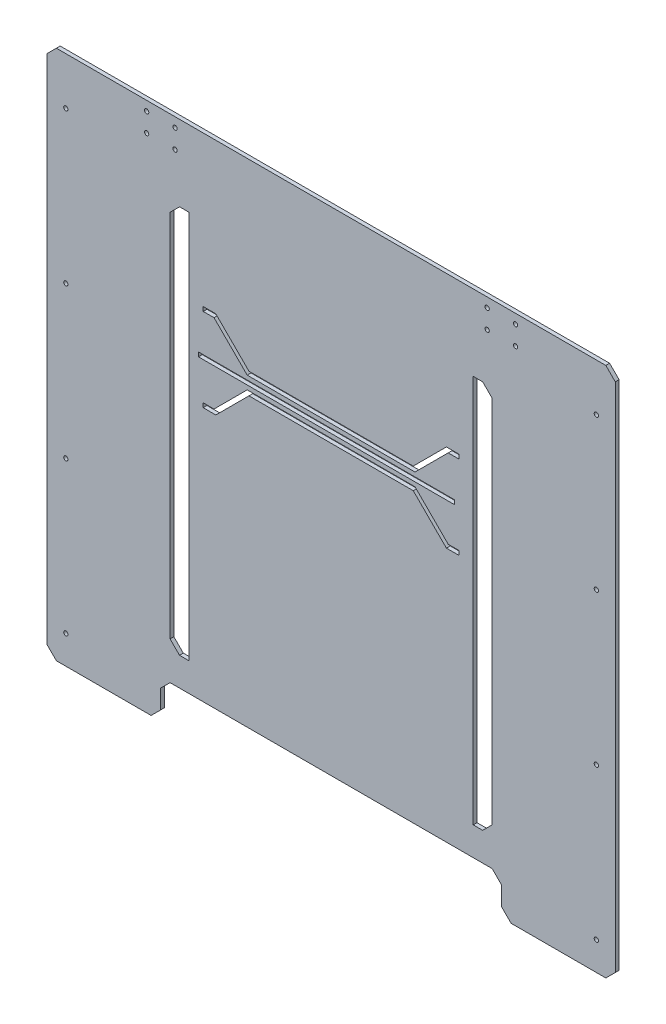
SolidWorks part; units mm, degrees
ref_plane "Front Plane" through (0, 0, 0) normal (0, 0, 1) x (1, 0, 0)
ref_plane "Top Plane" through (0, 0, 0) normal (0, 1, 0) x (1, 0, 0)
ref_plane "Right Plane" through (0, 0, 0) normal (1, 0, 0) x (0, 0, -1)
sketch "Sketch1" plane through (0, 0, 0) normal (0, 0, 1) x (1, 0, 0)
  line L0 (440.3197, -451.5188) -> (440.3197, -431.5188)
  line L1 (430.3197, -421.5188) -> (310.3197, -421.5188)
  line L2 (560.3197, -5.0048) -> (560.3197, 98.4812)
  line L3 (80.3197, -431.5188) -> (80.3197, -451.5188)
  line L4 (560.3197, 98.4812) -> (540.3197, 98.4812)
  line L5 (531.5264, 93.7193) -> (531.5264, -420.0048) construction
  line L6 (560.3197, -5.0048) -> (560.3197, -420.0048)
  line L7 (0.3197, 98.4812) -> (540.3197, 98.4812)
  line L8 (2.3197, -461.5188) -> (70.3197, -461.5188)
  line L9 (450.3197, -461.5188) -> (540.3197, -461.5188)
  line L10 (440.3197, -431.5188) -> (430.3197, -421.5188)
  line L11 (503.536, -23.973) -> (503.536, -80.4204) construction
  line L12 (-39.6803, -421.5188) -> (-39.6803, -5.0048)
  line L14 (450.3197, -461.5188) -> (440.3197, -451.5188)
  line L18 (0.3197, 98.4812) -> (-39.6803, 98.4812)
  line L19 (-39.6803, 98.4812) -> (-39.6803, -5.0048)
  line L20 (-39.6803, -421.5188) -> (-39.6803, -451.5188)
  line L21 (-29.6803, -461.5188) -> (2.3197, -461.5188)
  line L22 (560.3197, -420.0048) -> (560.3197, -451.5188)
  line L23 (550.3197, -461.5188) -> (540.3197, -461.5188)
  line L24 (90.3197, -421.5188) -> (80.3197, -431.5188)
  line L25 (80.3197, -451.5188) -> (70.3197, -461.5188)
  line L26 (560.3197, -451.5188) -> (550.3197, -461.5188)
  line L27 (-39.6803, -451.5188) -> (-29.6803, -461.5188)
  line L31 (210.3197, -421.5188) -> (90.3197, -421.5188)
  line L34 (310.3197, -421.5188) -> (210.3197, -421.5188)
  point P0 (440.3197, -461.5188)
  point P5 (440.3197, -421.5188)
  point P27 (-39.6803, -461.5188)
  point P28 (560.3197, -461.5188)
  point P29 (80.3197, -421.5188)
  point P30 (80.3197, -461.5188)
  point P42 (300.3197, -421.5188)
  point P46 (220.3197, -421.5188)
  dimension "D1" = 560
  dimension "D2" = 10
  dimension "D3" = 600
  dimension "D4" = 120
  dimension "D9" = 120
  dimension "D19" = 40
extrude "Boss-Extrude1" add sketch "Sketch1" along normal blind 4
sketch "Sketch3" plane through (0, 0, 0) normal (0, 0, -1) x (-1, 0, 0)
  line L1 (-410.3197, -391.5188) -> (-420.3197, -391.5188)
  line L2 (-410.3197, -391.5188) -> (-410.3197, 18.4812)
  line L3 (-410.3197, 18.4812) -> (-420.3197, 18.4812)
  line L4 (-430.3197, -381.5188) -> (-430.3197, 8.4812)
  line L5 (-420.3197, -391.5188) -> (-430.3197, -381.5188)
  line L6 (-420.3197, 18.4812) -> (-430.3197, 8.4812)
  line L7 (-560.3197, 98.4812) -> (39.6803, 98.4812) construction
  line L8 (-90.3197, -421.5188) -> (-430.3197, -421.5188) construction
  line L9 (-260.3197, -421.5188) -> (-260.3197, -274.4779) construction
  line L10 (-100.3197, 18.4812) -> (-90.3197, 8.4812)
  line L11 (-100.3197, -391.5188) -> (-90.3197, -381.5188)
  line L12 (-90.3197, -381.5188) -> (-90.3197, 8.4812)
  line L13 (-110.3197, 18.4812) -> (-100.3197, 18.4812)
  line L14 (-110.3197, -391.5188) -> (-110.3197, 18.4812)
  line L15 (-110.3197, -391.5188) -> (-100.3197, -391.5188)
  line L17 (-560.3197, -451.5188) -> (-560.3197, 98.4812) construction
  point P1 (-430.3197, 18.4812)
  point P3 (-430.3197, -391.5188)
  point P22 (-90.3197, -391.5188)
  point P23 (-90.3197, 18.4812)
  dimension "D1" = 20
  dimension "D2" = 80
  dimension "D3" = 30
  dimension "D5" = 130
extrude "Cut-Extrude2" cut sketch "Sketch3" against normal blind 10
sketch "Sketch4" plane through (0, 0, 0) normal (0, 0, -1) x (-1, 0, 0)
  line L6 (-390.3197, -104.1791) -> (-120.3197, -104.1791)
  line L8 (-390.3197, -108.6791) -> (-120.3197, -108.6791)
  line L11 (-260.3197, -104.1791) -> (-260.3197, -60.3431) construction
  line L13 (-100.3197, -106.4291) -> (-92.2726, -106.4291) construction
  line L16 (-390.3197, -104.1791) -> (-390.3197, -108.6791)
  line L20 (-410.3197, -391.5188) -> (-410.3197, 18.4812) construction
  line L35 (-120.3197, -104.1791) -> (-120.3197, -108.6791)
  dimension "D1" = 20
extrude "Cut-Extrude5" cut sketch "Sketch4" against normal blind 10
sketch "Sketch5" plane through (0, 0, 0) normal (0, 0, -1) x (-1, 0, 0)
  line L0 (-171.7435, -99.6791) -> (-260.3197, -99.6791)
  line L1 (-260.3197, -99.6791) -> (-260.3197, -95.1791)
  line L2 (-260.3197, -95.1791) -> (-173.6074, -95.1791)
  line L3 (-173.6074, -95.1791) -> (-138.6074, -60.1791)
  line L4 (-138.6074, -60.1791) -> (-125.3197, -60.1791)
  line L5 (-125.3197, -60.1791) -> (-125.3197, -64.6791)
  line L6 (-125.3197, -64.6791) -> (-136.7435, -64.6791)
  line L7 (-136.7435, -64.6791) -> (-171.7435, -99.6791)
  line L8 (-120.3197, -104.1791) -> (-390.3197, -104.1791) construction
  line L9 (-110.3197, 18.4812) -> (-110.3197, -391.5188) construction
  dimension "D1" = 4.5
  dimension "D2" = 4.5
  dimension "D3" = 4.5
  dimension "D4" = 35
  dimension "D5" = 35
  dimension "D6" = 4.5
  dimension "D7" = 15
extrude "Cut-Extrude6" cut sketch "Sketch5" against normal blind 10
mirror "Mirror3" about plane through (260.3197, -99.6791, 10) normal (1, 0, 0) of "Cut-Extrude6"
ref_plane "Plane1" through (0, -106.4291, 0) normal (0, -1, 0) x (-1, 0, 0)
mirror "Mirror9" about plane through (0, -106.4291, 0) normal (0, -1, 0) of "Cut-Extrude6", "Mirror3"
chamfer "Chamfer1" distance 10 angle 45 2 edges at (-39.6803, 98.4812, 2) (560.3197, 98.4812, 2)
sketch "Sketch6" plane through (0, 0, 0) normal (0, 0, -1) x (-1, 0, 0)
  line L0 (-560.3197, -451.5188) -> (-560.3197, 88.4812) construction
  line L1 (-550.3197, 98.4812) -> (29.6803, 98.4812) construction
  circle A0 centre (-540.3197, 48.4812) radius 2.25
  circle A1 centre (-540.3197, -111.5188) radius 2.25
  circle A2 centre (-540.3197, -271.5188) radius 2.25
  circle A3 centre (-540.3197, -431.5188) radius 2.25
  dimension "D2" = 4.5
  dimension "D1" = 20
  dimension "D3" = 50
  dimension "D4" = 4
extrude "Cut-Extrude7" cut sketch "Sketch6" against normal blind 10
ref_plane "Plane2" through (260.3197, 0, 0) normal (1, 0, 0) x (0, 0, -1)
mirror "Mirror10" about plane through (260.3197, 0, 0) normal (1, 0, 0) of "Cut-Extrude7"
sketch "Sketch7" plane through (0, 0, 4) normal (0, 0, 1) x (1, 0, 0)
  line L0 (65.6049, 88.4812) -> (95.6049, 88.4812) construction
  line L1 (95.6049, 88.4812) -> (95.6049, 68.4812) construction
  line L2 (95.6049, 68.4812) -> (65.6049, 68.4812) construction
  circle A0 centre (65.6049, 88.4812) radius 2.25
  circle A1 centre (65.6049, 88.4812) radius 2.25 construction
  circle A2 centre (95.6049, 88.4812) radius 2.25
  circle A3 centre (95.6049, 68.4812) radius 2.25
  circle A4 centre (65.6049, 68.4812) radius 2.25
  dimension "D1" = 4.5
  dimension "D2" = 30
  dimension "D3" = 20
  dimension "D4" = 30
extrude "Cut-Extrude8" cut sketch "Sketch7" against normal blind 10
mirror "Mirror11" about plane through (260.3197, 0, 0) normal (1, 0, 0) of "Cut-Extrude8"
